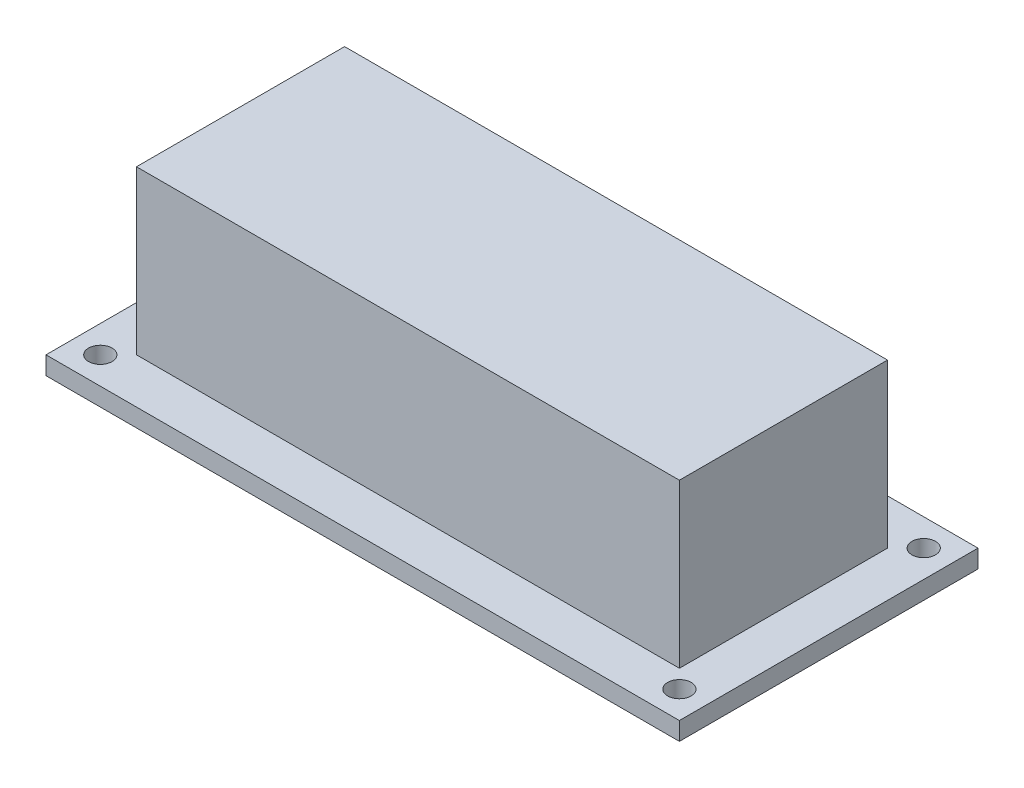
SolidWorks part; units mm, degrees
ref_plane "Front Plane" through (0, 0, 0) normal (0, 0, 1) x (1, 0, 0)
ref_plane "Top Plane" through (0, 0, 0) normal (0, 1, 0) x (1, 0, 0)
ref_plane "Right Plane" through (0, 0, 0) normal (1, 0, 0) x (0, 0, -1)
sketch "Sketch2" plane through (0, 0, 0) normal (0, 1, 0) x (1, 0, 0)
  line L1 (-44.45, 20.955) -> (44.45, 20.955)
  line L2 (-44.45, 20.955) -> (-44.45, -20.955)
  line L3 (-44.45, -20.955) -> (44.45, -20.955)
  line L4 (44.45, 20.955) -> (44.45, -20.955)
  line L5 (-44.45, 20.955) -> (44.45, -20.955) construction
  line L6 (-44.45, -20.955) -> (44.45, 20.955) construction
  point P0 (0, 0)
  dimension "D1" = 41.91
  dimension "D2" = 88.9
extrude "Boss-Extrude1" add sketch "Sketch2" along normal blind 2.54
sketch "Sketch3" plane through (0, 0, 0) normal (0, 1, 0) x (1, 0, 0)
  line L0 (-44.45, 0) -> (44.45, 0) construction
  line L1 (-44.45, 20.955) -> (-44.45, -20.955) construction
  line L2 (44.45, -20.955) -> (44.45, 20.955) construction
  line L3 (0, 20.955) -> (0, -20.955) construction
  line L4 (44.45, 20.955) -> (-44.45, 20.955) construction
  line L5 (-44.45, -20.955) -> (44.45, -20.955) construction
  circle A0 centre (-40.64, 17.145) radius 1.651
  circle A1 centre (40.64, 17.145) radius 1.651
  circle A2 centre (40.64, -17.145) radius 1.651
  circle A3 centre (-40.64, -17.145) radius 1.651
  dimension "D1" = 3.302
  dimension "D2" = 81.28
  dimension "D3" = 34.29
extrude "Cut-Extrude2" cut sketch "Sketch3" along normal through all
sketch "Sketch4" plane through (0, 2.54, 0) normal (0, 1, 0) x (1, 0, 0)
  line L8 (38.1, -14.605) -> (38.1, 14.605)
  line L9 (38.1, 14.605) -> (-38.1, 14.605)
  line L10 (-38.1, 14.605) -> (-38.1, -14.605)
  line L11 (-38.1, -14.605) -> (38.1, -14.605)
  line L12 (38.1, -14.605) -> (38.1, 14.605)
  line L13 (38.1, 14.605) -> (-38.1, 14.605)
  line L14 (-38.1, 14.605) -> (-38.1, -14.605)
  line L15 (-38.1, -14.605) -> (38.1, -14.605)
  dimension "D1" = 6.35
extrude "Boss-Extrude2" add sketch "Sketch4" along normal blind 22.86
